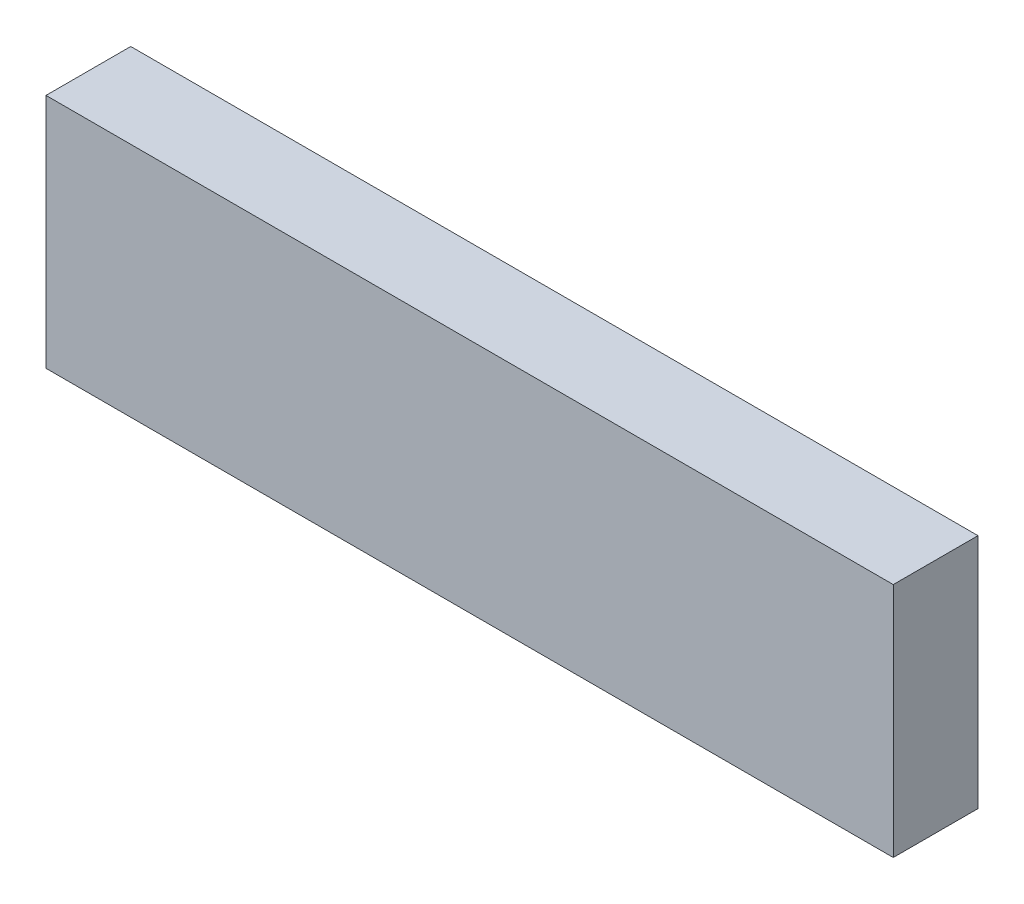
SolidWorks part; units mm, degrees
ref_plane "Plan de face" through (0, 0, 0) normal (0, 0, 1) x (1, 0, 0)
ref_plane "Plan de dessus" through (0, 0, 0) normal (0, 1, 0) x (1, 0, 0)
ref_plane "Plan de droite" through (0, 0, 0) normal (1, 0, 0) x (0, 0, -1)
sketch "Esquisse1" plane through (0, 0, 0) normal (0, 0, 1) x (1, 0, 0)
  line L1 (0, 0) -> (50, 0)
  line L2 (0, 0) -> (0, 13.95)
  line L3 (0, 13.95) -> (50, 13.95)
  line L4 (50, 0) -> (50, 13.95)
  dimension "D1" = 50
  dimension "D2" = 13.95
extrude "Boss.-Extru.1" add sketch "Esquisse1" along normal blind 5
